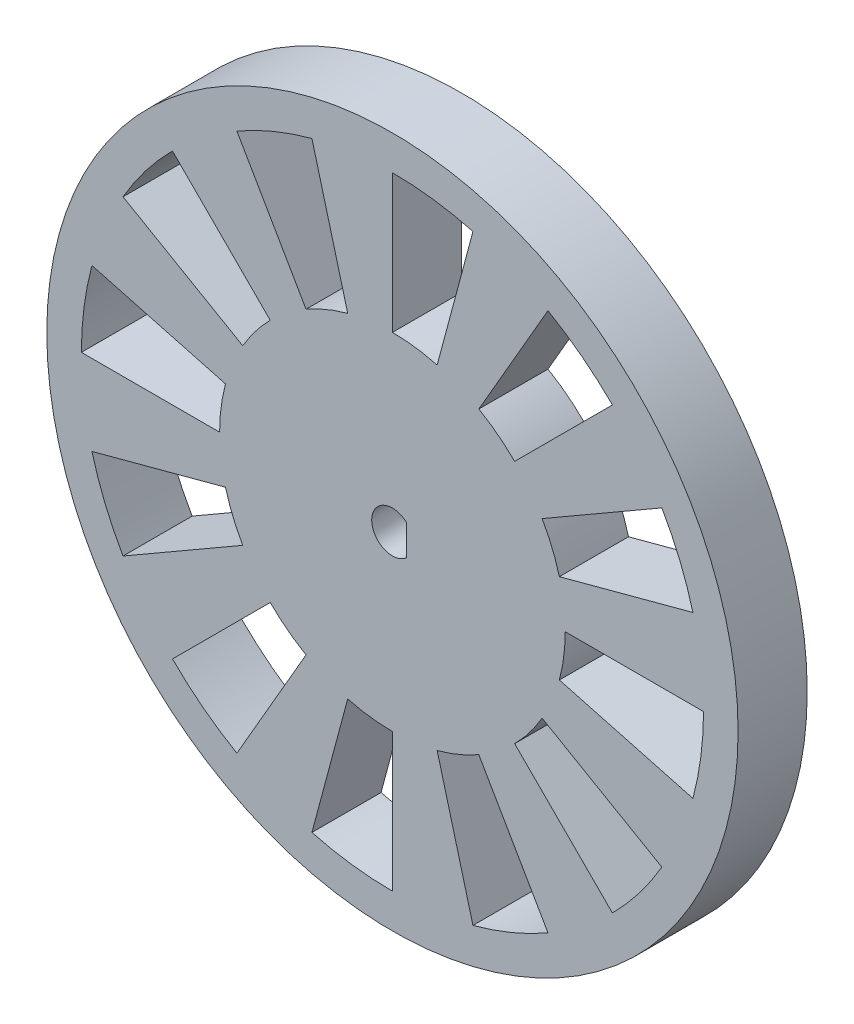
SolidWorks part; units mm, degrees
ref_plane "前基準面" through (0, 0, 0) normal (0, 0, 1) x (1, 0, 0)
ref_plane "上基準面" through (0, 0, 0) normal (0, 1, 0) x (1, 0, 0)
ref_plane "右基準面" through (0, 0, 0) normal (1, 0, 0) x (0, 0, -1)
sketch "草圖2" plane through (0, 0, 0) normal (0, 0, 1) x (1, 0, 0)
  line L0 (0, 12.5) -> (0, 22.5)
  line L1 (3.2352, 12.0741) -> (5.8234, 21.7333)
  line L2 (6.25, 10.8253) -> (11.25, 19.4856)
  line L3 (8.8388, 8.8388) -> (15.9099, 15.9099)
  line L4 (10.8253, 6.25) -> (19.4856, 11.25)
  line L5 (12.0741, 3.2352) -> (21.7333, 5.8234)
  line L6 (12.5, 0) -> (22.5, 0)
  line L7 (12.0741, -3.2352) -> (21.7333, -5.8234)
  line L8 (10.8253, -6.25) -> (19.4856, -11.25)
  line L9 (8.8388, -8.8388) -> (15.9099, -15.9099)
  line L10 (6.25, -10.8253) -> (11.25, -19.4856)
  line L11 (3.2352, -12.0741) -> (5.8234, -21.7333)
  line L12 (0, -12.5) -> (0, -22.5)
  line L13 (-3.2352, -12.0741) -> (-5.8234, -21.7333)
  line L14 (-6.25, -10.8253) -> (-11.25, -19.4856)
  line L15 (-8.8388, -8.8388) -> (-15.9099, -15.9099)
  line L16 (-10.8253, -6.25) -> (-19.4856, -11.25)
  line L17 (-12.0741, -3.2352) -> (-21.7333, -5.8234)
  line L18 (-12.5, 0) -> (-22.5, 0)
  line L19 (-12.0741, 3.2352) -> (-21.7333, 5.8234)
  line L20 (-10.8253, 6.25) -> (-19.4856, 11.25)
  line L21 (-8.8388, 8.8388) -> (-15.9099, 15.9099)
  line L22 (-6.25, 10.8253) -> (-11.25, 19.4856)
  line L23 (-3.2352, 12.0741) -> (-5.8234, 21.7333)
  line L24 (1, -1.118) -> (1, 1.118)
  circle A0 centre (0, 0) radius 25
  arc A1 (-5.8234, 21.7333) -> (-11.25, 19.4856) centre (0, 0) ccw
  arc A2 (-3.2352, 12.0741) -> (-6.25, 10.8253) centre (0, 0) ccw
  arc A3 (-8.8388, 8.8388) -> (-10.8253, 6.25) centre (0, 0) ccw
  arc A4 (-15.9099, 15.9099) -> (-19.4856, 11.25) centre (0, 0) ccw
  arc A5 (-21.7333, 5.8234) -> (-22.5, 0) centre (0, 0) ccw
  arc A6 (-12.0741, 3.2352) -> (-12.5, 0) centre (0, 0) ccw
  arc A7 (-21.7333, -5.8234) -> (-19.4856, -11.25) centre (0, 0) ccw
  arc A8 (-12.0741, -3.2352) -> (-10.8253, -6.25) centre (0, 0) ccw
  arc A9 (-8.8388, -8.8388) -> (-6.25, -10.8253) centre (0, 0) ccw
  arc A10 (-15.9099, -15.9099) -> (-11.25, -19.4856) centre (0, 0) ccw
  arc A11 (-5.8234, -21.7333) -> (0, -22.5) centre (0, 0) ccw
  arc A12 (-3.2352, -12.0741) -> (0, -12.5) centre (0, 0) ccw
  arc A13 (3.2352, -12.0741) -> (6.25, -10.8253) centre (0, 0) ccw
  arc A14 (5.8234, -21.7333) -> (11.25, -19.4856) centre (0, 0) ccw
  arc A15 (15.9099, -15.9099) -> (19.4856, -11.25) centre (0, 0) ccw
  arc A16 (8.8388, -8.8388) -> (10.8253, -6.25) centre (0, 0) ccw
  arc A17 (12.0741, -3.2352) -> (12.5, 0) centre (0, 0) ccw
  arc A18 (12.0741, 3.2352) -> (10.8253, 6.25) centre (0, 0) ccw
  arc A19 (8.8388, 8.8388) -> (6.25, 10.8253) centre (0, 0) ccw
  arc A20 (3.2352, 12.0741) -> (0, 12.5) centre (0, 0) ccw
  arc A21 (5.8234, 21.7333) -> (0, 22.5) centre (0, 0) ccw
  arc A22 (15.9099, 15.9099) -> (11.25, 19.4856) centre (0, 0) ccw
  arc A23 (21.7333, 5.8234) -> (19.4856, 11.25) centre (0, 0) ccw
  arc A24 (21.7333, -5.8234) -> (22.5, 0) centre (0, 0) ccw
  arc A25 (1, 1.118) -> (1, -1.118) centre (0, 0) ccw
  point P55 (0, 0)
  dimension "D1" = 50
  dimension "D2" = 45
  dimension "D3" = 25
  dimension "D5" = 3
  dimension "D6" = 1
  dimension "D4" = 24
extrude "填料-伸長1" add sketch "草圖2" along normal blind 5
